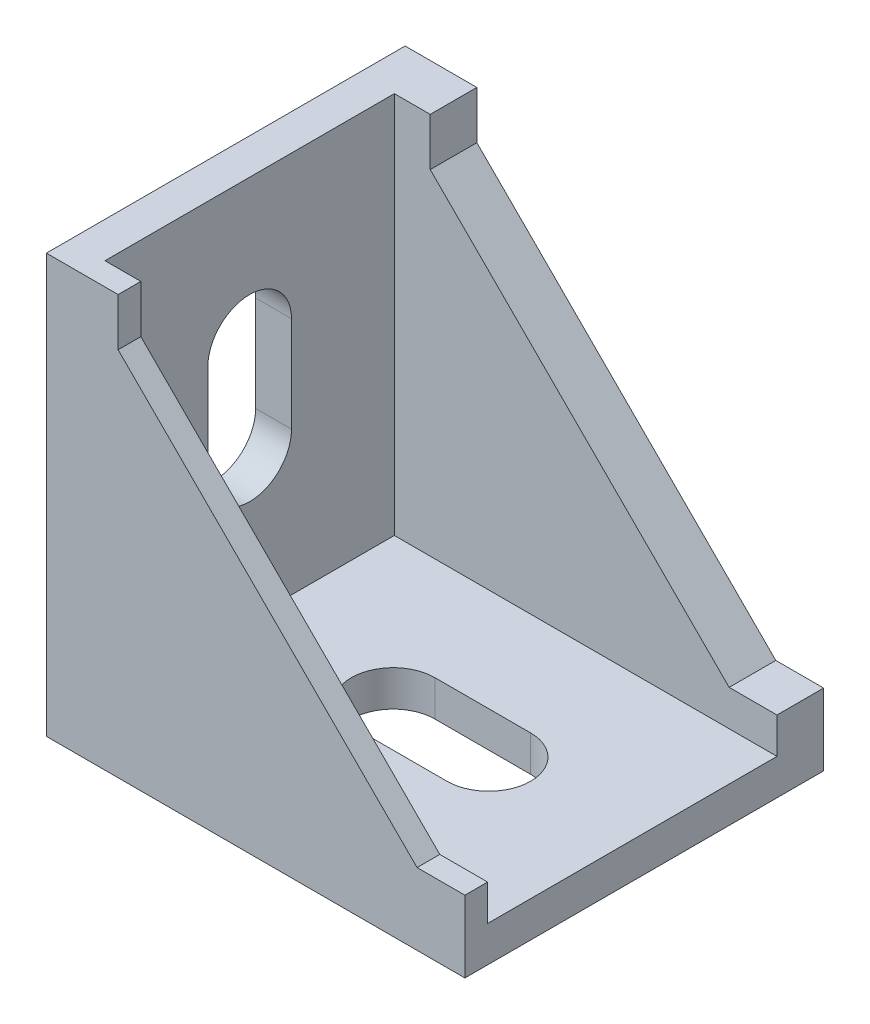
SolidWorks part; units mm, degrees
ref_plane "Front Plane" through (0, 0, 0) normal (0, 0, 1) x (1, 0, 0)
ref_plane "Top Plane" through (0, 0, 0) normal (0, 1, 0) x (1, 0, 0)
ref_plane "Right Plane" through (0, 0, 0) normal (1, 0, 0) x (0, 0, -1)
sketch "Sketch1" plane through (0, 0, 0) normal (0, 0, 1) x (1, 0, 0)
  line L0 (0, 17.5) -> (0, 0)
  line L1 (0, 0) -> (17.5, 0)
  line L2 (17.5, 0) -> (17.5, 3)
  line L3 (17.5, 3) -> (15.5, 3)
  line L4 (15.5, 3) -> (3, 15.5)
  line L5 (3, 15.5) -> (3, 17.5)
  line L6 (3, 17.5) -> (0, 17.5)
  dimension "D1" = 17.5
  dimension "D2" = 17.5
  dimension "D3" = 3
  dimension "D4" = 3
  dimension "D5" = 15.5
  dimension "D6" = 45
extrude "Boss-Extrude1" add sketch "Sketch1" against normal blind 15
sketch "Sketch4" plane through (0, 0, 0) normal (0, 0, 1) x (1, 0, 0)
  line L0 (1.5, 17.5) -> (1.5, 1.5)
  line L1 (3, 17.5) -> (0, 17.5) construction
  line L2 (1.5, 1.5) -> (17.5, 1.5)
  line L3 (17.5, 0) -> (17.5, 3) construction
  line L4 (17.5, 1.5) -> (17.5, 3)
  line L5 (17.5, 3) -> (3, 17.5)
  line L6 (3, 17.5) -> (1.5, 17.5)
  line L9 (0, 17.5) -> (0, 0) construction
  line L10 (0, 0) -> (17.5, 0) construction
  dimension "D1" = 1.5
  dimension "D2" = 1.5
extrude "Cut-Extrude1" cut sketch "Sketch4" against normal mid plane 12.1 from offset 7 offset against normal yes
sketch "Sketch5" plane through (0, 1.5, 0) normal (0, 1, 0) x (1, 0, 0)
  line L0 (17.5, 7) -> (1.5, 7) construction
  line L2 (7.5, 7) -> (11.5, 7) construction
  line L5 (17.5, 13.05) -> (17.5, 0.95) construction
  line L6 (1.5, 13.05) -> (1.5, 0.95) construction
  line L8 (7.5, 8.75) -> (11.5, 8.75)
  line L9 (7.5, 5.25) -> (11.5, 5.25)
  arc A2 (7.5, 8.75) -> (7.5, 5.25) centre (7.5, 7) ccw
  arc A3 (11.5, 5.25) -> (11.5, 8.75) centre (11.5, 7) ccw
  point P8 (9.5, 7)
  dimension "D1" = 4
extrude "Cut-Extrude2" cut sketch "Sketch5" against normal through all both and the other way through all
sketch "Sketch6" plane through (1.5, 0, 0) normal (1, 0, 0) x (0, 0, -1)
  line L0 (7, 17.5) -> (7, 1.5) construction
  line L1 (13.05, 17.5) -> (0.95, 17.5) construction
  line L2 (13.05, 1.5) -> (0.95, 1.5) construction
  line L3 (7, 7.5) -> (7, 11.5) construction
  line L5 (5.25, 7.5) -> (5.25, 11.5)
  line L6 (8.75, 7.5) -> (8.75, 11.5)
  arc A0 (5.25, 7.5) -> (8.75, 7.5) centre (7, 7.5) ccw
  arc A1 (8.75, 11.5) -> (5.25, 11.5) centre (7, 11.5) ccw
  point P10 (7, 9.5)
  dimension "D1" = 4
extrude "Cut-Extrude3" cut sketch "Sketch6" against normal through all both
